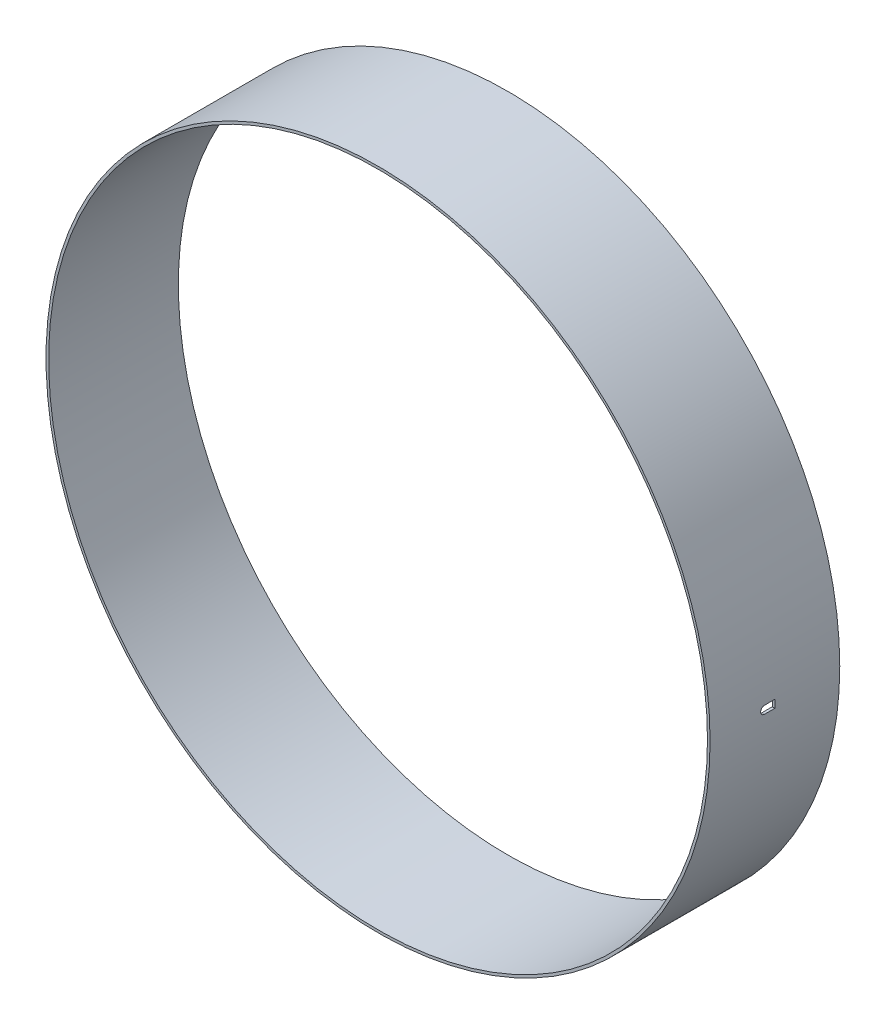
SolidWorks part; units mm, degrees
ref_plane "前视基准面" through (0, 0, 0) normal (0, 0, 1) x (1, 0, 0)
ref_plane "上视基准面" through (0, 0, 0) normal (0, 1, 0) x (1, 0, 0)
ref_plane "右视基准面" through (0, 0, 0) normal (1, 0, 0) x (0, 0, -1)
sketch "草图1" plane through (0, 0, 0) normal (0, 0, 1) x (1, 0, 0)
  circle A0 centre (0, 0) radius 64
  circle A1 centre (0, 0) radius 63.5
  dimension "D1" = 128
  dimension "D2" = 127
extrude "凸台-拉伸1" add sketch "草图1" along normal blind 25
sketch "草图2" plane through (0, 0, 0) normal (1, 0, 0) x (0, 0, -1)
  line L0 (-14.5, -0.75) -> (-12.5, -0.75)
  line L1 (-12.5, -0.75) -> (-12.5, 0.75)
  line L2 (-12.5, 0.75) -> (-14.5, 0.75)
  arc A0 (-14.5, 0.75) -> (-14.5, -0.75) centre (-14.5, 0) ccw
  dimension "D1" = 1.5
  dimension "D2" = 2
  dimension "D3" = 14.5
  dimension "D4" = 0
extrude "切除-拉伸1" cut sketch "草图2" along normal blind 2000
